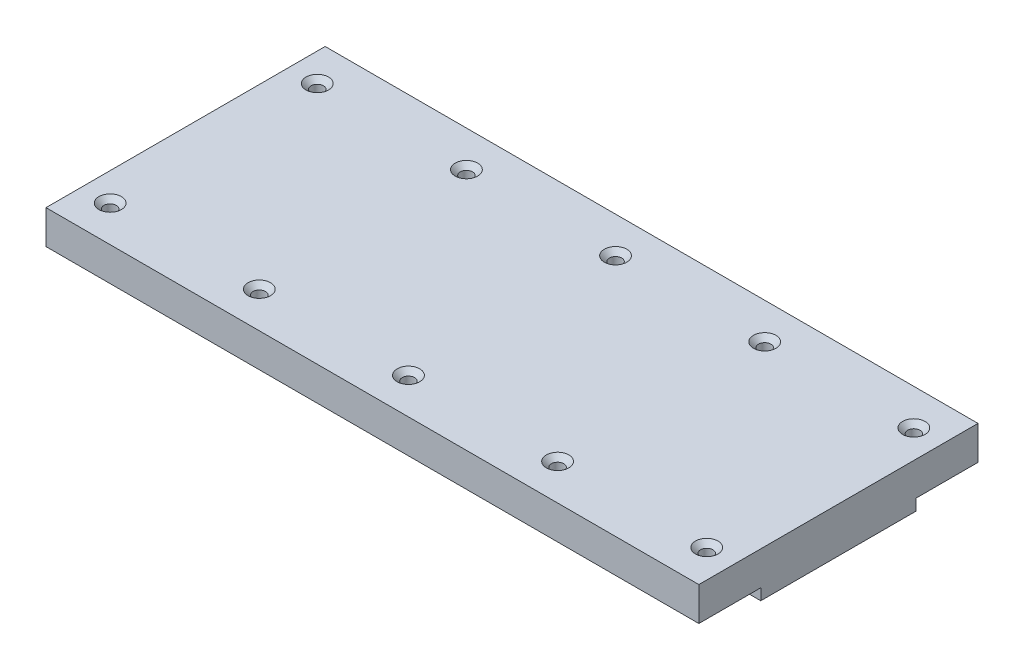
SolidWorks part; units mm, degrees
ref_plane "Front Plane" through (0, 0, 0) normal (0, 0, 1) x (1, 0, 0)
ref_plane "Top Plane" through (0, 0, 0) normal (0, 1, 0) x (1, 0, 0)
ref_plane "Right Plane" through (0, 0, 0) normal (1, 0, 0) x (0, 0, -1)
sketch "Sketch2" plane through (0, 0, 0) normal (1, 0, 0) x (0, 0, -1)
  line L0 (-124, 0) -> (124, 0)
  line L1 (124, 0) -> (124, -30)
  line L2 (124, -30) -> (69, -30)
  line L3 (69, -30) -> (69, -40)
  line L4 (69, -40) -> (-69, -40)
  line L5 (-69, -40) -> (-69, -30)
  line L6 (-69, -30) -> (-124, -30)
  line L7 (-124, -30) -> (-124, 0)
  point P4 (0, 0)
  point P6 (0, 0)
  point P12 (0, -40)
  dimension "D1" = 40
  dimension "D2" = 138
  dimension "D3" = 10
  dimension "D4" = 248
extrude "Boss-Extrude1" add sketch "Sketch2" along normal mid plane 580
sketch "Sketch4" plane through (0, 0, 0) normal (0, 1, 0) x (1, 0, 0)
  line L0 (-290, 124) -> (-290, -124) construction
  line L1 (-383.3716, 0) -> (383.3716, 0) construction
  point P0 (-265, 92)
  point P1 (265, -92)
  point P5 (-132.5, 92)
  point P7 (0, 92)
  point P8 (132.5, 92)
  point P9 (265, 92)
  point P12 (0, 0)
  point P13 (132.5, -92)
  point P14 (0, -92)
  point P15 (-132.5, -92)
  point P16 (-265, -92)
  point P17 (0, 0)
  dimension "D1" = 92
  dimension "D2" = 25
  dimension "D3" = 5
hole_wizard "CSK for M10 Flat Head Machine Screw1" positions "3DSketch1" profile "Sketch5" countersink size "M10" standard "ANSI Metric"
sketch3d "3DSketch1"
  point P0 (-265, 0, -92)
  point P3 (-132.5, 0, -92)
  point P6 (0, 0, -92)
  point P9 (132.5, 0, -92)
  point P12 (265, 0, -92)
  point P15 (265, 0, 92)
  point P18 (132.5, 0, 92)
  point P21 (0, 0, 92)
  point P24 (-132.5, 0, 92)
  point P27 (-265, 0, 92)
sketch "Sketch5" plane through (-265, 0, -92) normal (1, 0, 0) x (0, 0, 1)
  line L0 (0, 0) -> (0, 59)
  line L1 (0, 59) -> (5.5, 55.6953)
  line L2 (5.5, 55.6953) -> (5.5, 4.5)
  line L3 (5.5, 4.5) -> (10, 0)
  line L5 (10, 0) -> (0, 0)
  line L6 (-5.5, 4.5) -> (-10, 0) construction
  line L10 (0, 59) -> (-5.5, 55.6953) construction
  line L11 (0, -6.35) -> (0, 107.95) construction
  dimension "Hole Dia." = 11
  dimension "Hole Depth" = 59
  dimension "Near C'Sink Dia." = 20
  dimension "Near C'Sink Angle" = 90
  dimension "Drill Angle" = 118
